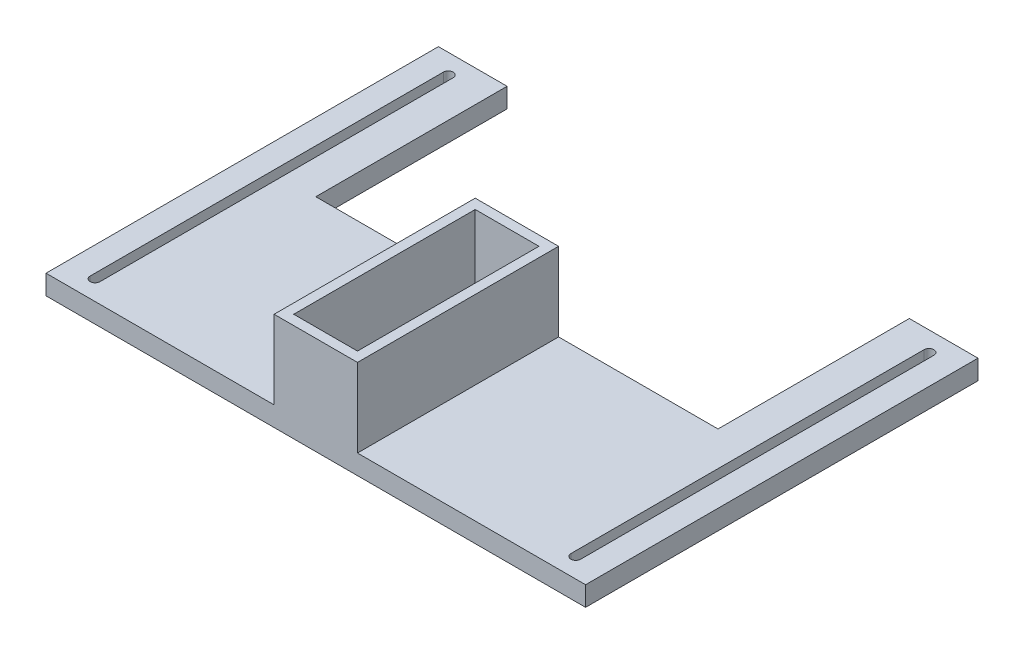
SolidWorks part; units mm, degrees
ref_plane "Front Plane" through (0, 0, 0) normal (0, 0, 1) x (1, 0, 0)
ref_plane "Top Plane" through (0, 0, 0) normal (0, 1, 0) x (1, 0, 0)
ref_plane "Right Plane" through (0, 0, 0) normal (1, 0, 0) x (0, 0, -1)
sketch "Sketch1" plane through (0, 0, 0) normal (0, 1, 0) x (1, 0, 0)
  line L1 (-3.25, -9.25) -> (3.25, -9.25)
  line L2 (-3.25, -9.25) -> (-3.25, 9.25)
  line L3 (-3.25, 9.25) -> (3.25, 9.25)
  line L4 (3.25, -9.25) -> (3.25, 9.25)
  line L5 (-3.25, -9.25) -> (3.25, 9.25) construction
  line L6 (-3.25, 9.25) -> (3.25, -9.25) construction
  point P0 (0, 0)
  dimension "D1" = 6.5
  dimension "D2" = 18.5
extrude "Extrude-Thin1" add sketch "Sketch1" along normal blind 8 thin
sketch "Sketch2" plane through (0, 0, 0) normal (0, -1, 0) x (1, 0, 0)
  line L0 (20.5, -29.75) -> (20.5, -10.25)
  line L5 (-27.5, -29.75) -> (-27.5, 10.25)
  line L6 (-27.5, 10.25) -> (27.5, 10.25)
  line L7 (27.5, 10.25) -> (27.5, -29.75)
  line L8 (27.5, -29.75) -> (20.5, -29.75)
  line L9 (20.5, -10.25) -> (-20.5, -10.25)
  line L10 (-20.5, -10.25) -> (-20.5, -29.75)
  line L11 (-20.5, -29.75) -> (-27.5, -29.75)
  line L12 (-4.25, 10.25) -> (4.25, 10.25) construction
  line L13 (4.25, -10.25) -> (-4.25, -10.25) construction
  line L14 (0, -4.4) -> (0, 4.4) construction
  point P12 (0, 10.25)
  dimension "D1" = 55
  dimension "D2" = 40
  dimension "D3" = 7
extrude "Boss-Extrude1" add sketch "Sketch2" along normal blind 2
sketch "Sketch3" plane through (0, -2, 0) normal (0, -1, 0) x (1, 0, 0)
  line L0 (-24.5, 8.25) -> (-24.5, -27.75) construction
  line L1 (-24, 8.25) -> (-24, -27.75)
  line L2 (-25, 8.25) -> (-25, -27.75)
  line L3 (-24.5, 8.25) -> (-24.5, 10.25) construction
  line L4 (27.5, 10.25) -> (-27.5, 10.25) construction
  line L5 (-24.5, -27.75) -> (-24.5, -29.75) construction
  line L6 (-27.5, -29.75) -> (-20.5, -29.75) construction
  line L7 (0, -5.5) -> (0, 5.5) construction
  arc A0 (-24, 8.25) -> (-25, 8.25) centre (-24.5, 8.25) ccw
  arc A1 (-25, -27.75) -> (-24, -27.75) centre (-24.5, -27.75) ccw
  point P2 (-24.5, -9.75)
  dimension "D1" = 0.5
  dimension "D2" = 2
  dimension "D3" = 24.5
extrude "Cut-Extrude1" cut sketch "Sketch3" against normal up to next
mirror "Mirror1" about plane through (0, 0, 0) normal (1, 0, 0) of "Cut-Extrude1"
